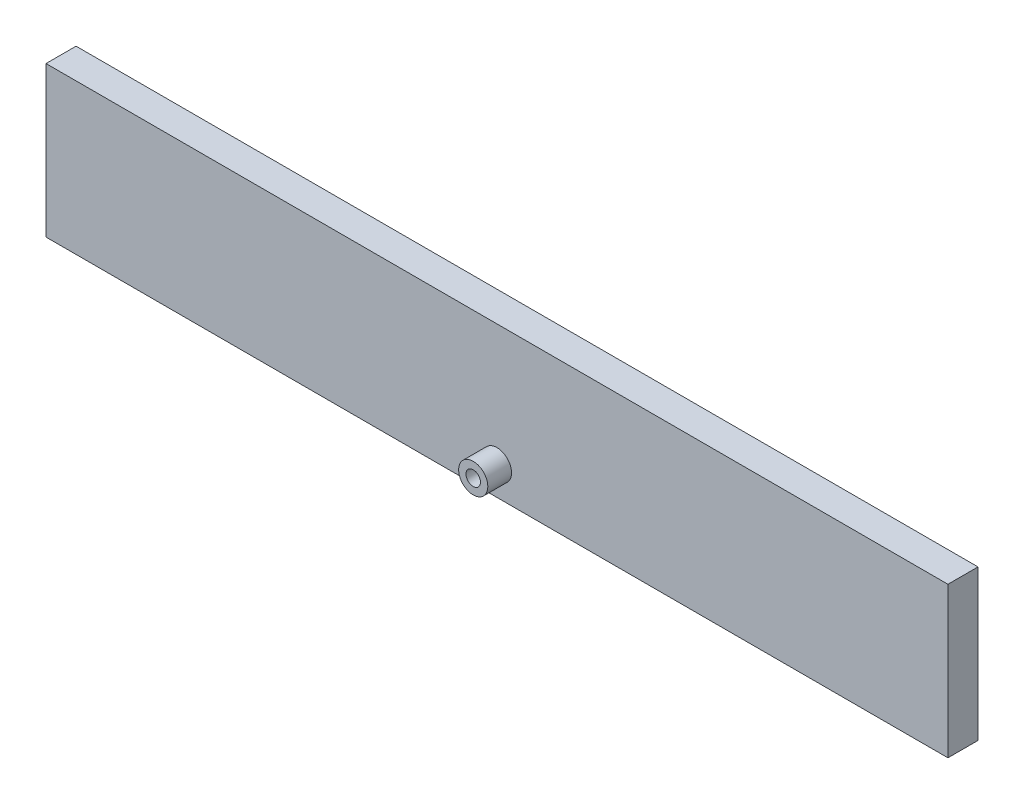
SolidWorks part; units mm, degrees
ref_plane "Front Plane" through (0, 0, 0) normal (0, 0, 1) x (1, 0, 0)
ref_plane "Top Plane" through (0, 0, 0) normal (0, 1, 0) x (1, 0, 0)
ref_plane "Right Plane" through (0, 0, 0) normal (1, 0, 0) x (0, 0, -1)
sketch "Sketch1" plane through (0, 0, 0) normal (0, 0, 1) x (1, 0, 0)
  line L1 (-300, 50) -> (300, 50)
  line L2 (-300, 50) -> (-300, -50)
  line L3 (-300, -50) -> (300, -50)
  line L4 (300, 50) -> (300, -50)
  line L5 (-300, 50) -> (300, -50) construction
  line L6 (-300, -50) -> (300, 50) construction
  point P0 (0, 0)
  dimension "D1" = 600
  dimension "D2" = 100
extrude "Boss-Extrude1" add sketch "Sketch1" along normal blind 20
sketch "Sketch2" plane through (0, 0, 20) normal (0, 0, 1) x (1, 0, 0)
  line L0 (-300, -50) -> (300, -50) construction
  line L1 (-300, 50) -> (-300, -50) construction
  circle A0 centre (0, -30.95) radius 4.826
  circle A1 centre (0, -30.95) radius 9.7
  dimension "D1" = 9.652
  dimension "D2" = 19.05
  dimension "D3" = 300
  dimension "D4" = 19.4
extrude "Boss-Extrude2" add sketch "Sketch2" along normal blind 15.8
